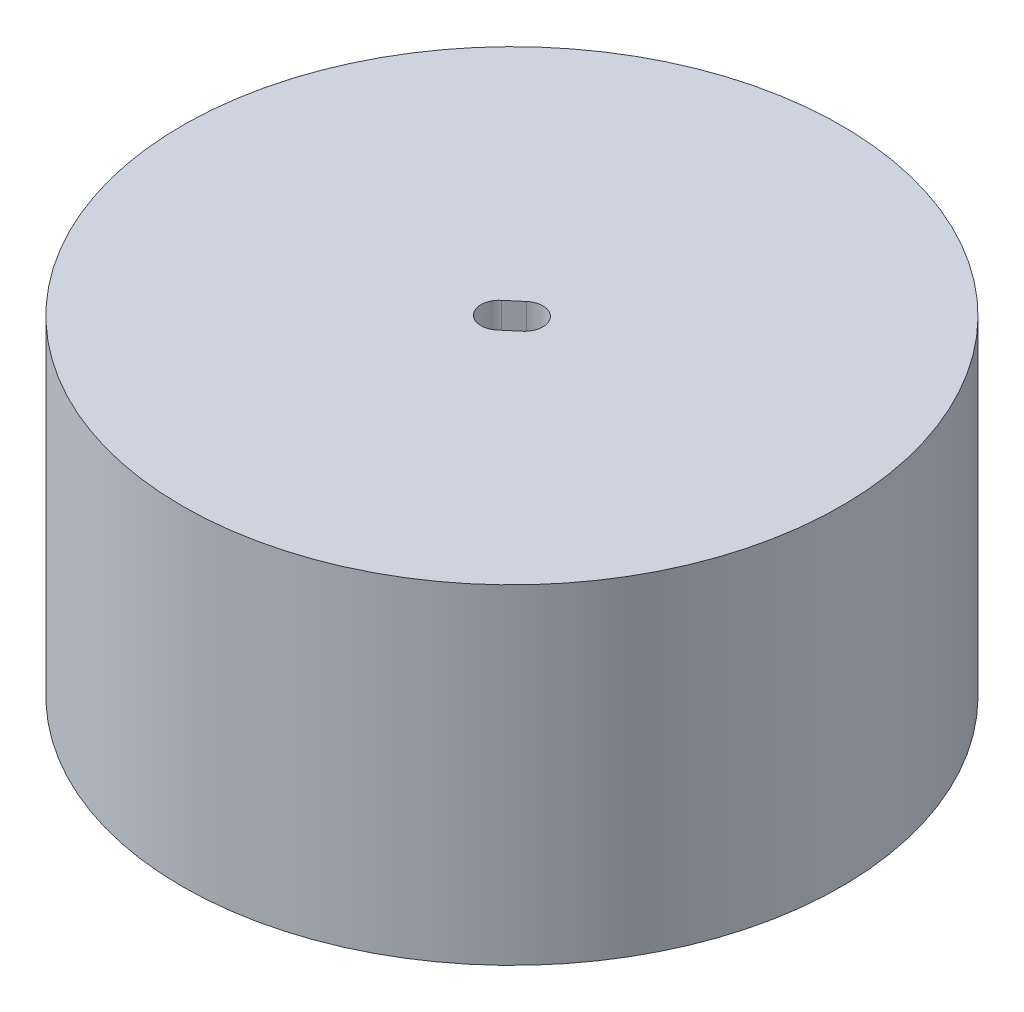
SolidWorks part; units mm, degrees
ref_plane "Front Plane" through (0, 0, 0) normal (0, 0, 1) x (1, 0, 0)
ref_plane "Top Plane" through (0, 0, 0) normal (0, 1, 0) x (1, 0, 0)
ref_plane "Right Plane" through (0, 0, 0) normal (1, 0, 0) x (0, 0, -1)
sketch "Sketch1" plane through (0, 0, 0) normal (0, 1, 0) x (1, 0, 0)
  circle A0 centre (0, 0) radius 32
  dimension "D1" = 64
extrude "Boss-Extrude1" add sketch "Sketch1" along normal blind 32
sketch "Sketch2" plane through (0, 32, 0) normal (0, 1, 0) x (1, 0, 0)
  line L0 (-0.6641, -0.562) -> (0.6641, 0.562) construction
  line L1 (-1.8107, 0.793) -> (-0.4824, 1.917)
  line L2 (0.4824, -1.917) -> (1.8107, -0.793)
  arc A0 (-1.8107, 0.793) -> (0.4824, -1.917) centre (-0.6641, -0.562) ccw
  arc A1 (1.8107, -0.793) -> (-0.4824, 1.917) centre (0.6641, 0.562) ccw
  point P2 (0, 0)
  dimension "D1" = 3.55
  dimension "D2" = 1.74
extrude "Cut-Extrude1" cut sketch "Sketch2" against normal through all
